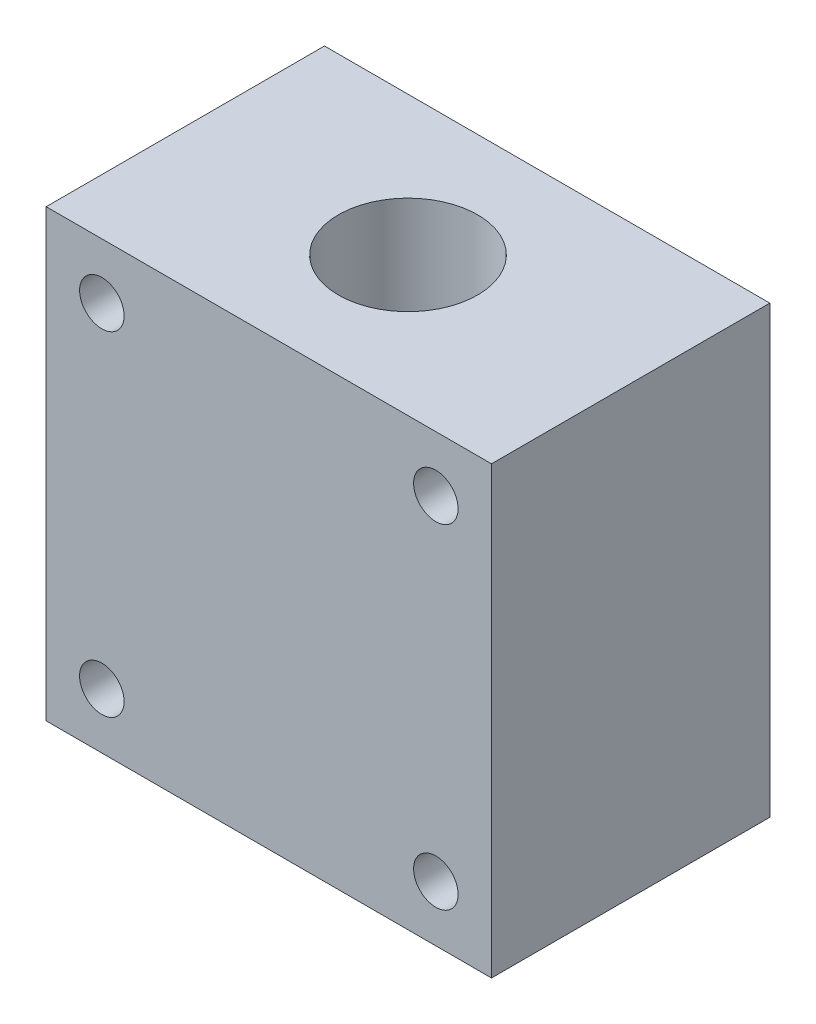
SolidWorks part; units mm, degrees
ref_plane "Front Plane" through (0, 0, 0) normal (0, 0, 1) x (1, 0, 0)
ref_plane "Top Plane" through (0, 0, 0) normal (0, 1, 0) x (1, 0, 0)
ref_plane "Right Plane" through (0, 0, 0) normal (1, 0, 0) x (0, 0, -1)
sketch "Sketch1" plane through (0, 0, 0) normal (0, 1, 0) x (1, 0, 0)
  line L1 (40, -25) -> (-40, -25)
  line L2 (40, -25) -> (40, 25)
  line L3 (40, 25) -> (-40, 25)
  line L4 (-40, -25) -> (-40, 25)
  line L5 (40, -25) -> (-40, 25) construction
  line L6 (40, 25) -> (-40, -25) construction
  point P0 (0, 0)
  dimension "D1" = 50
  dimension "D2" = 80
extrude "Boss-Extrude1" add sketch "Sketch1" along normal blind 80
sketch "Sketch2" plane through (0, 80, 0) normal (0, 1, 0) x (1, 0, 0)
  circle A0 centre (0, 0) radius 12.5
  dimension "D1" = 25
extrude "Cut-Extrude1" cut sketch "Sketch2" against normal through all
sketch "Sketch3" plane through (0, 0, 25) normal (0, 0, 1) x (1, 0, 0)
  line L0 (-40, 40) -> (40, 40) construction
  line L1 (30, 10) -> (-30, 10)
  line L2 (30, 10) -> (30, 70)
  line L3 (30, 70) -> (-30, 70)
  line L4 (-30, 10) -> (-30, 70)
  line L5 (30, 10) -> (-30, 70) construction
  line L6 (30, 70) -> (-30, 10) construction
  line L7 (-40, 80) -> (-40, 0) construction
  line L8 (40, 80) -> (40, 0) construction
  line L9 (0, 80) -> (0, 0) construction
  line L10 (-40, 80) -> (40, 80) construction
  line L11 (-40, 0) -> (40, 0) construction
  circle A0 centre (-30, 70) radius 4
  circle A1 centre (-30, 10) radius 4
  circle A2 centre (30, 10) radius 4
  circle A3 centre (30, 70) radius 4
  point P0 (0, 40)
  point P21 (0, 0)
  dimension "D3" = 8
  dimension "D1" = 60
  dimension "D2" = 60
extrude "Cut-Extrude2" cut sketch "Sketch3" against normal through all contours L3 A0 L4 | L4 A1 L1 | L1 A2 L2 | L2 A3 L3 | L4 A0 L3 | L1 A1 L4 | L2 A2 L1 | L3 A3 L2
